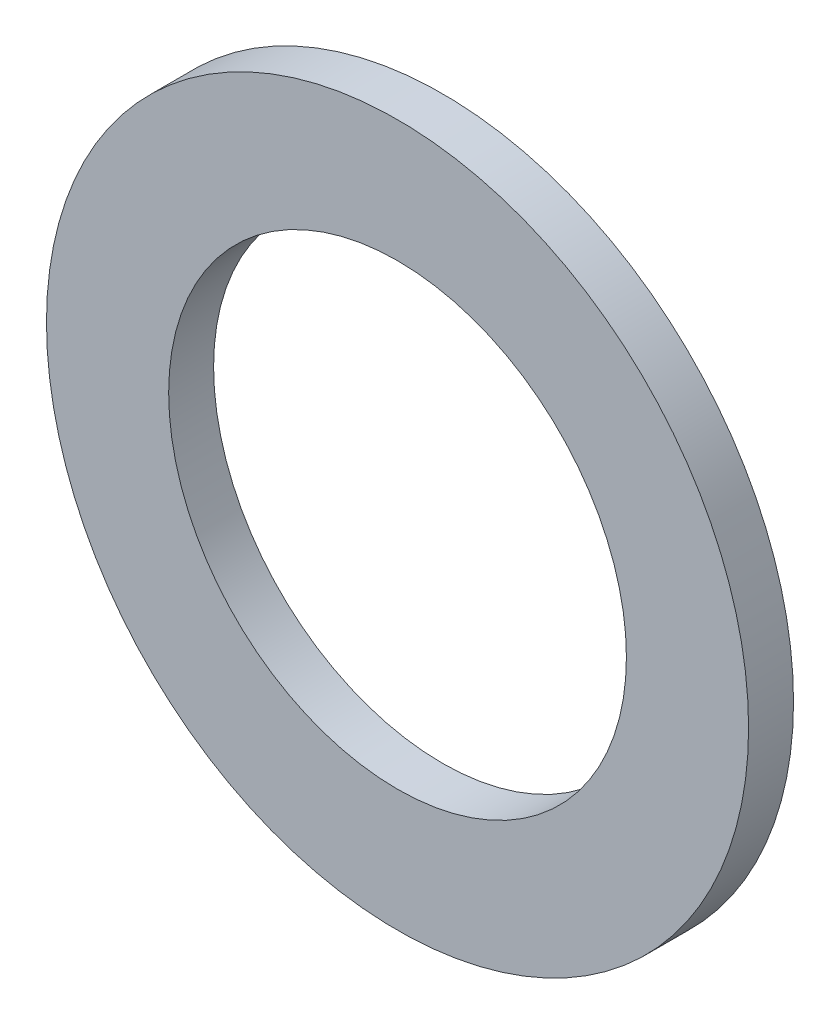
SolidWorks part; units mm, degrees
material "6061-T6 (SS)"
ref_plane "Front Plane" through (0, 0, 0) normal (0, 0, 1) x (1, 0, 0)
ref_plane "Top Plane" through (0, 0, 0) normal (0, 1, 0) x (1, 0, 0)
ref_plane "Right Plane" through (0, 0, 0) normal (1, 0, 0) x (0, 0, -1)
sketch "Sketch1" plane through (0, 0, 0) normal (1, 0, 0) x (0, 0, -1)
  line L0 (0, 7.9375) -> (0, 5.175)
  line L1 (0, 7.9375) -> (1.016, 7.9375)
  line L2 (0, 5.175) -> (1.016, 5.175)
  line L3 (1.016, 7.9375) -> (1.016, 5.175)
  line L4 (-3.1107, 0) -> (9.8662, 0) construction
  dimension "D1" = 10.35
  dimension "D2" = 15.875
  dimension "D3" = 1.016
revolve "Revolve1" add sketch "Sketch1" angle 360 about L4
